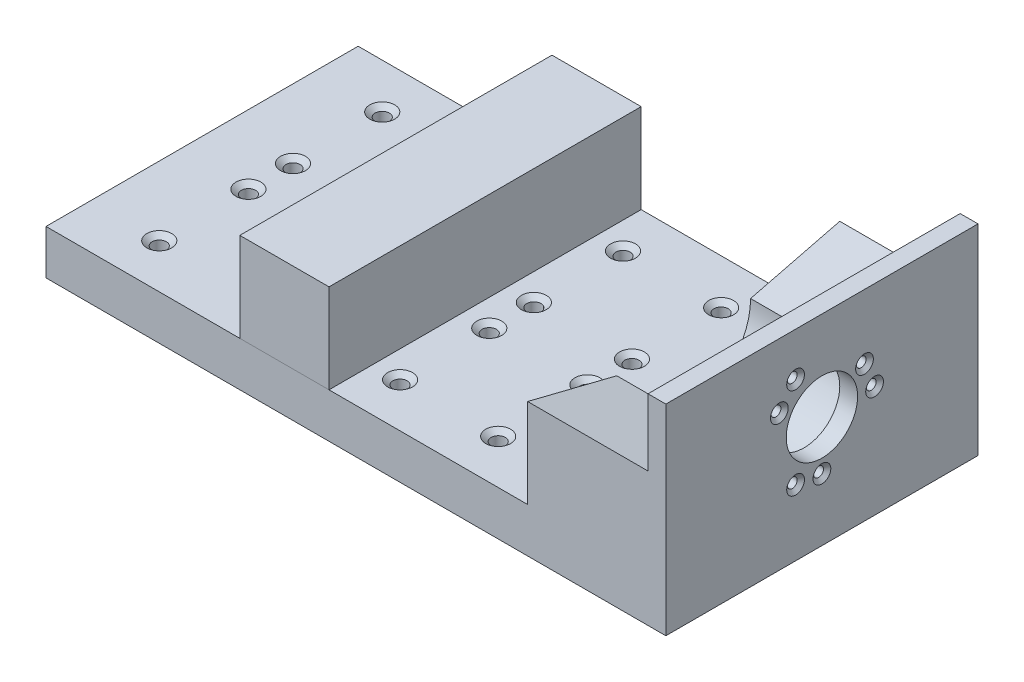
SolidWorks part; units mm, degrees
ref_plane "Front Plane" through (0, 0, 0) normal (0, 0, 1) x (1, 0, 0)
ref_plane "Top Plane" through (0, 0, 0) normal (0, 1, 0) x (1, 0, 0)
ref_plane "Right Plane" through (0, 0, 0) normal (1, 0, 0) x (0, 0, -1)
sketch "Sketch1" plane through (0, 0, 0) normal (0, 1, 0) x (1, 0, 0)
  line L1 (0, 0) -> (-139.7, 0)
  line L2 (0, 0) -> (0, -88.9)
  line L3 (0, -88.9) -> (-139.7, -88.9)
  line L4 (-139.7, 0) -> (-139.7, -88.9)
  dimension "D1" = 88.9
  dimension "D2" = 139.7
extrude "Boss-Extrude1" add sketch "Sketch1" along normal blind 76.2
sketch "Sketch2" plane through (0, 0, 0) normal (1, 0, 0) x (0, 0, -1)
  line L0 (-44.45, 63.5) -> (-44.45, 0) construction
  line L1 (-88.9, 38.1) -> (0, 38.1) construction
  line L2 (0, 76.2) -> (0, 0) construction
  line L3 (-88.9, 0) -> (0, 0) construction
  line L4 (-88.9, 31.75) -> (0, 31.75) construction
  line L5 (-88.9, 76.2) -> (-88.9, 0) construction
  line L6 (-63.5, 31.75) -> (-88.9, 38.1)
  line L7 (-25.4, 31.75) -> (0, 38.1)
  arc A1 (-63.5, 31.75) -> (-25.4, 31.75) centre (-44.45, 31.75) ccw
  point P1 (0, 0)
extrude "Cut-Extrude1" cut sketch "Sketch2" along direction (-1, 0, 0) on the side against the normal blind 34.29 and the other way through all
sketch "Sketch4" plane through (0, 0, 0) normal (1, 0, 0) x (0, 0, -1)
  line L0 (-88.9, 38.1) -> (-63.5, 31.75)
  line L1 (-25.4, 31.75) -> (0, 38.1)
  line L2 (0, 38.1) -> (-25.4, 31.75) construction
  line L8 (0, 0) -> (0, 38.1)
  line L9 (0, 38.1) -> (-25.4, 31.75)
  line L10 (-63.5, 31.75) -> (-88.9, 38.1)
  line L11 (-88.9, 38.1) -> (-88.9, 0)
  line L12 (-88.9, 0) -> (0, 0)
  line L13 (0, 0) -> (0, 38.1)
  line L16 (-88.9, 38.1) -> (-88.9, 0)
  line L17 (-88.9, 0) -> (0, 0)
  arc A0 (-63.5, 31.75) -> (-25.4, 31.75) centre (-44.45, 31.75) ccw construction
  arc A1 (-63.5, 31.75) -> (-25.4, 31.75) centre (-44.45, 31.75) ccw
  arc A3 (-63.5, 31.75) -> (-25.4, 31.75) centre (-44.45, 31.75) ccw
  dimension "D1" = 0
extrude "Boss-Extrude2" add sketch "Sketch4" along normal blind 5.08
sketch "Sketch5" plane through (5.08, 0, 0) normal (1, 0, 0) x (0, 0, -1)
  line L0 (-88.9, 57.15) -> (-88.9, 38.1)
  line L1 (-88.9, 76.2) -> (-88.9, 38.1) construction
  line L2 (-88.9, 57.15) -> (0, 57.15)
  line L3 (0, 76.2) -> (0, 38.1) construction
  line L4 (0, 57.15) -> (0, 38.1)
  circle A0 centre (-44.45, 31.75) radius 19.05
  circle A1 centre (-44.45, 31.75) radius 10.16
  line M4 (0, 38.1) -> (-25.4, 31.75)
  arc M5 (-25.4, 31.75) -> (-63.5, 31.75) centre (-44.45, 31.75) cw
  line M6 (-63.5, 31.75) -> (-88.9, 38.1)
extrude "Boss-Extrude3" add sketch "Sketch5" against normal blind 5.08 contours A0 L4 L2 L0 M4 M6 | A0 A1 M5
sketch "Sketch6" plane through (0, 76.2, 0) normal (0, 1, 0) x (1, 0, 0)
  line L1 (-139.7, 0) -> (-34.29, 0)
  line L2 (-139.7, 0) -> (-139.7, -88.9)
  line L3 (-139.7, -88.9) -> (-34.29, -88.9)
  line L4 (-34.29, 0) -> (-34.29, -88.9)
extrude "Cut-Extrude2" cut sketch "Sketch6" against normal blind 63.5 and the other way through all
sketch "Sketch7" plane through (-139.7, 0, 0) normal (-1, 0, 0) x (0, 0, 1)
  line L1 (0, 12.7) -> (88.9, 12.7)
  line L2 (0, 12.7) -> (0, 0)
  line L3 (0, 0) -> (88.9, 0)
  line L4 (88.9, 12.7) -> (88.9, 0)
extrude "Boss-Extrude4" add sketch "Sketch7" along normal blind 31.75
sketch "Sketch8" plane through (0, 12.7, 0) normal (0, 1, 0) x (1, 0, 0)
  line L0 (-102.87, 0) -> (-102.87, -88.9) construction
  line L1 (-171.45, -88.9) -> (-171.45, 0) construction
  line L2 (-171.45, -44.45) -> (-34.29, -44.45) construction
  line L3 (-34.29, 0) -> (-171.45, 0) construction
  line L4 (-171.45, -88.9) -> (-34.29, -88.9) construction
  line L5 (-171.45, 0) -> (-171.45, -6.35)
  line L6 (-171.45, -88.9) -> (-171.45, -82.55)
  line L7 (-171.45, -6.35) -> (-34.29, -6.35) construction
  line L8 (-117.5048, -6.35) -> (-158.1448, -6.35)
  line L9 (-34.29, -44.45) -> (-34.29, 0) construction
  line L10 (-171.45, -82.55) -> (-34.29, -82.55) construction
  line L11 (-34.29, -63.5) -> (-34.29, -88.9) construction
  line L12 (-117.5048, -6.35) -> (-117.5048, -44.45)
  line L13 (-48.9248, -6.35) -> (-89.5648, -6.35)
  line L15 (-48.9248, -44.45) -> (-89.5648, -44.45)
  line L16 (-89.5648, -6.35) -> (-89.5648, -44.45)
  line L18 (-158.1448, -6.35) -> (-158.1448, -44.45)
  line L20 (-117.5048, -44.45) -> (-117.5048, -82.55)
  line L21 (-117.5048, -82.55) -> (-158.1448, -82.55)
  line L22 (-158.1448, -44.45) -> (-158.1448, -82.55)
  line L23 (-48.9248, -44.45) -> (-89.5648, -44.45)
  line L24 (-48.9248, -44.45) -> (-48.9248, -82.55)
  line L25 (-48.9248, -82.55) -> (-89.5648, -82.55)
  line L26 (-89.5648, -44.45) -> (-89.5648, -82.55)
  line L27 (-158.1448, -6.35) -> (-137.8248, -6.35)
  line L31 (-117.5048, -44.45) -> (-89.5648, -44.45)
  line L32 (-117.5048, -44.45) -> (-158.1448, -44.45)
  line L33 (-117.5048, -44.45) -> (-158.1448, -44.45)
  circle A0 centre (-123.8548, -12.7966) radius 2.032
  circle A1 centre (-151.7948, -12.7966) radius 2.032
  circle A2 centre (-151.7948, -38.1966) radius 2.032
  circle A3 centre (-123.8548, -38.1966) radius 2.032
  circle A4 centre (-123.8548, -50.8966) radius 2.032
  circle A5 centre (-151.7948, -50.8966) radius 2.032
  circle A6 centre (-151.7948, -76.2966) radius 2.032
  circle A7 centre (-123.8548, -76.2966) radius 2.032
  circle A8 centre (-55.2748, -12.7966) radius 2.032
  circle A9 centre (-83.2148, -12.7966) radius 2.032
  circle A10 centre (-83.2148, -38.1966) radius 2.032
  circle A11 centre (-55.2748, -38.1966) radius 2.032
  circle A12 centre (-55.2748, -50.8966) radius 2.032
  circle A13 centre (-83.2148, -50.8966) radius 2.032
  circle A14 centre (-83.2148, -76.2966) radius 2.032
  circle A15 centre (-55.2748, -76.2966) radius 2.032
  point P45 (-55.2748, -12.7966)
  point P47 (-123.8548, -12.7966)
  point P49 (-123.8548, -50.8966)
  point P51 (-151.7948, -12.7966)
  point P53 (-151.7948, -38.1966)
  point P55 (-123.8548, -38.1966)
  point P57 (-151.7948, -50.8966)
  point P59 (-151.7948, -76.2966)
  point P61 (-123.8548, -76.2966)
  point P64 (-55.2748, -50.8966)
  point P68 (-83.2148, -12.7966)
  point P70 (-83.2148, -38.1966)
  point P72 (-55.2748, -38.1966)
  point P74 (-83.2148, -50.8966)
  point P76 (-83.2148, -76.2966)
  point P78 (-55.2748, -76.2966)
  point P88 (-151.7948, -12.7966)
  point P90 (-123.8548, -12.7966)
  point P92 (-151.7948, -38.1966)
  point P94 (-123.8548, -38.1966)
  point P112 (-54.616, -10.8744)
  point P132 (-55.2748, -38.1966)
  dimension "D3" = 2
  dimension "D1" = 2
  dimension "D2" = 2
  dimension "D4" = 2
  dimension "D5" = 2
hole_wizard "CSK for #6 Flat Head Machine Screw (100)1" positions "Sketch8" profile "Sketch9" countersink size "#6" standard "ANSI Inch"
sketch "Sketch9" plane through (-55.2748, 12.7, 38.1966) normal (1, 0, 0) x (0, 0, 1)
  line L0 (0, 0) -> (0, 12.7)
  line L1 (0, 12.7) -> (2.032, 12.7)
  line L2 (2.032, 12.7) -> (2.032, 1.2681)
  line L3 (2.032, 1.2681) -> (3.5433, 0)
  line L5 (3.5433, 0) -> (0, 0)
  line L6 (-2.032, 1.2681) -> (-3.5433, 0) construction
  line L11 (0, -6.35) -> (0, 107.95) construction
  dimension "Thru Hole Dia." = 4.064
  dimension "Thru Hole Depth" = 12.7
  dimension "Near C'Sink Dia." = 7.0866
  dimension "Near C'Sink Angle" = 100
sketch "Sketch10" plane through (0, 12.7, 0) normal (0, 1, 0) x (1, 0, 0)
  line L0 (-116.2475, 0) -> (-90.8475, 0)
  line L1 (-34.29, 0) -> (-171.45, 0) construction
  line L2 (-171.45, -88.9) -> (-34.29, -88.9) construction
  line L3 (-116.2475, -88.9) -> (-90.8475, -88.9)
  line L4 (-116.2475, -88.9) -> (-116.2475, 0)
  line L5 (-90.8475, -88.9) -> (-90.8475, 0)
extrude "Boss-Extrude5" add sketch "Sketch10" along normal blind 25.4 separate body
sketch "Sketch11" plane through (5.08, 0, 0) normal (1, 0, 0) x (0, 0, -1)
  line L0 (-44.45, 50.8) -> (-44.45, 12.7) construction
  line L1 (-63.5, 31.75) -> (-25.4, 31.75) construction
  line L2 (-44.45, 31.75) -> (-53.975, 15.2522) construction
  circle A0 centre (-56.5743, 38.75) radius 1.5
  circle A2 centre (-44.45, 31.75) radius 10.16 construction
  circle A3 centre (-44.45, 31.75) radius 14 construction
  circle A4 centre (-44.45, 31.75) radius 15 construction
  circle A5 centre (-44.45, 31.75) radius 2.75 construction
  circle A6 centre (-44.45, 31.75) radius 19.05 construction
  circle A7 centre (-44.45, 17.75) radius 1.5
  circle A8 centre (-32.3257, 38.75) radius 1.5
  circle A9 centre (-51.95, 18.7596) radius 1.5
  circle A10 centre (-51.95, 44.7404) radius 1.5
  circle A11 centre (-29.45, 31.75) radius 1.5
  point P0 (-51.95, 18.7596)
  point P11 (-44.45, 17.75)
  point P17 (-56.5743, 38.75)
  point P19 (-32.3257, 38.75)
  point P21 (-44.45, 31.75)
  point P24 (-51.95, 44.7404)
  point P26 (-29.45, 31.75)
  point P28 (-44.45, 31.75)
  dimension "D1" = 3
  dimension "D2" = 3
hole_wizard "CSK for #3 Flat Head Machine Screw (100)1" positions "Sketch11" profile "Sketch12" countersink size "#3" standard "ANSI Inch"
sketch "Sketch12" plane through (5.08, 18.7596, 51.95) normal (0, 1, 0) x (0, 0, -1)
  line L0 (0, 0) -> (0, 26.2394)
  line L1 (0, 26.2394) -> (1.397, 25.4)
  line L2 (1.397, 25.4) -> (1.397, 0.9484)
  line L3 (1.397, 0.9484) -> (2.5273, 0)
  line L5 (2.5273, 0) -> (0, 0)
  line L6 (-1.397, 0.9484) -> (-2.5273, 0) construction
  line L10 (0, 26.2394) -> (-1.397, 25.4) construction
  line L11 (0, -6.35) -> (0, 107.95) construction
  dimension "Hole Dia." = 2.794
  dimension "Hole Depth" = 25.4
  dimension "Near C'Sink Dia." = 5.0546
  dimension "Near C'Sink Angle" = 100
  dimension "Drill Angle" = 118
